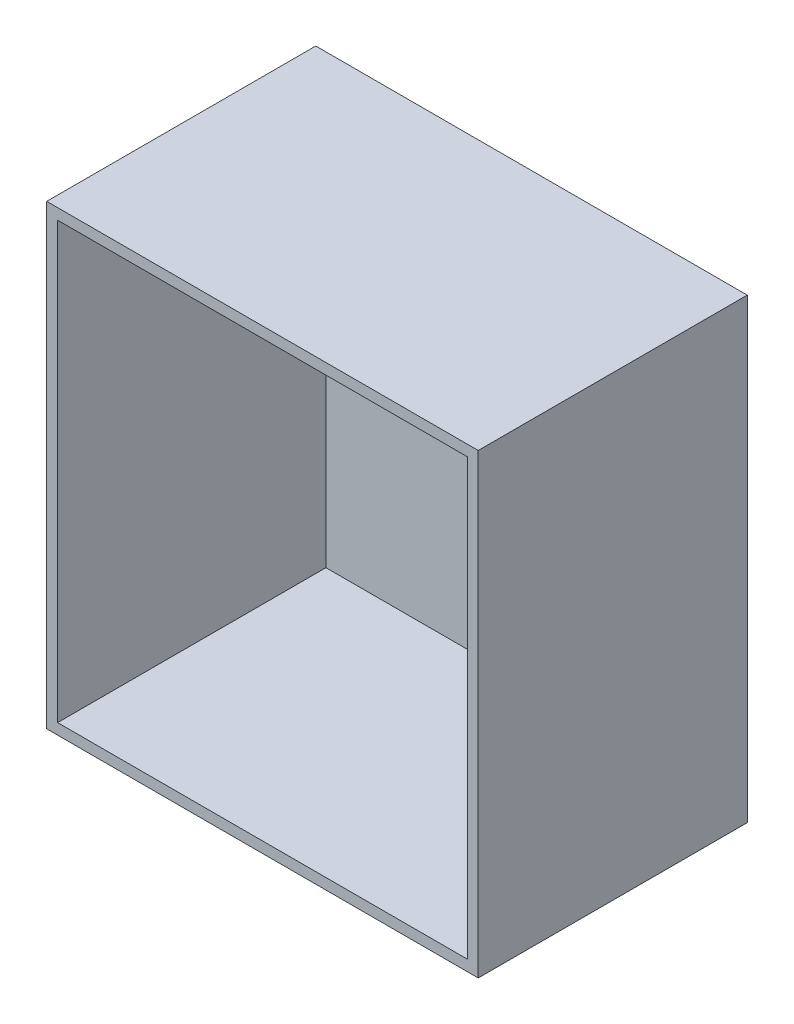
SolidWorks part; units mm, degrees
ref_plane "Front Plane" through (0, 0, 0) normal (0, 0, 1) x (1, 0, 0)
ref_plane "Top Plane" through (0, 0, 0) normal (0, 1, 0) x (1, 0, 0)
ref_plane "Right Plane" through (0, 0, 0) normal (1, 0, 0) x (0, 0, -1)
sketch "Sketch1" plane through (0, 0, 0) normal (0, 0, 1) x (1, 0, 0)
  line L0 (-297.5, -315) -> (297.5, -315)
  line L1 (-282.5, -300) -> (282.5, -300)
  line L2 (-282.5, -300) -> (-282.5, 300)
  line L3 (-282.5, 300) -> (282.5, 300)
  line L4 (282.5, -300) -> (282.5, 300)
  line L5 (-282.5, -300) -> (282.5, 300) construction
  line L6 (-282.5, 300) -> (282.5, -300) construction
  line L7 (297.5, -315) -> (297.5, 315)
  line L8 (-297.5, 315) -> (297.5, 315)
  line L9 (-297.5, -315) -> (-297.5, 315)
  point P0 (0, 0)
  dimension "D1" = 565
  dimension "D2" = 600
  dimension "D3" = 15
extrude "Boss-Extrude3" add sketch "Sketch1" along normal blind 370
sketch "Sketch3" plane through (0, 0, 0) normal (0, 0, -1) x (-1, 0, 0)
  line L4 (297.5, -315) -> (297.5, 315)
  line L5 (297.5, 315) -> (-297.5, 315)
  line L6 (-297.5, 315) -> (-297.5, -315)
  line L7 (-297.5, -315) -> (297.5, -315)
  line L8 (297.5, -315) -> (297.5, 315)
  line L9 (297.5, 315) -> (-297.5, 315)
  line L10 (-297.5, 315) -> (-297.5, -315)
  line L11 (-297.5, -315) -> (297.5, -315)
  dimension "D1" = 0
extrude "Boss-Extrude4" add sketch "Sketch3" along normal blind 1
